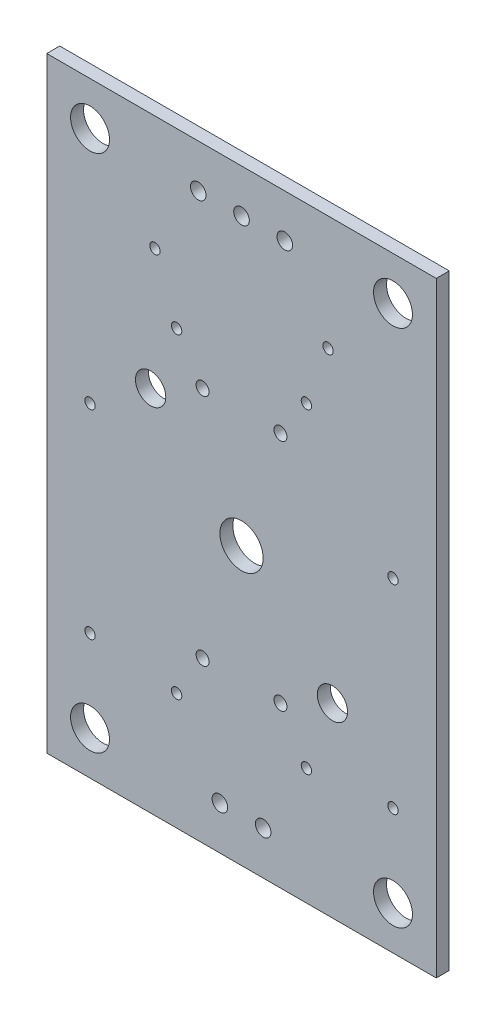
SolidWorks part; units mm, degrees
ref_plane "Спереди" through (0, 0, 0) normal (0, 0, 1) x (1, 0, 0)
ref_plane "Сверху" through (0, 0, 0) normal (0, 1, 0) x (1, 0, 0)
ref_plane "Справа" through (0, 0, 0) normal (1, 0, 0) x (0, 0, -1)
sketch "Эскиз1" plane through (0, 0, 0) normal (0, 0, 1) x (1, 0, 0)
  line L0 (0, 0) -> (72.8035, 0) construction
  line L1 (0, 0) -> (0, 51.7634) construction
  line L3 (-22.5, -35) -> (22.5, -35)
  line L4 (-22.5, -35) -> (-22.5, 35)
  line L5 (-22.5, 35) -> (22.5, 35)
  line L6 (22.5, -35) -> (22.5, 35)
  circle A0 centre (-17.5, 30) radius 2.25
  circle A1 centre (17.5, 30) radius 2.25
  circle A2 centre (17.5, -30) radius 2.25
  circle A3 centre (-17.5, -30) radius 2.25
  circle A4 centre (0, -3) radius 2.5
  circle A5 centre (-10.5, 7.5) radius 1.75
  circle A6 centre (10.5, -13.5) radius 1.75
  circle A7 centre (-5, 30) radius 0.9
  circle A8 centre (0, 30) radius 0.9
  circle A9 centre (5, 30) radius 0.9
  circle A10 centre (-2.5, -30) radius 0.9
  circle A11 centre (2.5, -30) radius 0.9
  circle A12 centre (-4.5, -16.5) radius 0.75
  circle A13 centre (-4.5, 10.5) radius 0.75
  circle A14 centre (4.5, -16.5) radius 0.75
  circle A15 centre (4.5, 10.5) radius 0.75
  dimension "D3" = 4.5
  dimension "D5" = 5
  dimension "D7" = 5
  dimension "D8" = 3.5
  dimension "D15" = 1.8
  dimension "D18" = 1.8
  dimension "D21" = 1.5
  dimension "D1" = 70
  dimension "D2" = 45
  dimension "D4" = 5
  dimension "D6" = 32
  dimension "D9" = 12
  dimension "D10" = 42.5
  dimension "D11" = 33
  dimension "D12" = 21.5
  dimension "D13" = 65
  dimension "D14" = 17.5
  dimension "D16" = 5
  dimension "D17" = 20
  dimension "D19" = 18
  dimension "D20" = 18.5
  dimension "D22" = 18
  dimension "D23" = 45.5
extrude "Вытянуть1" add sketch "Эскиз1" along normal blind 1.5
sketch "Эскиз2" plane through (0, 0, 1.5) normal (0, 0, 1) x (1, 0, 0)
  line L0 (0, 0) -> (0, 37.2524) construction
  line L1 (-22.5, 35) -> (-22.5, -35) construction
  line L2 (-22.5, -35) -> (22.5, -35) construction
  line L3 (-17.5, -20.5) -> (-17.5, -4.0913) construction
  circle A0 centre (-17.5, -20.5) radius 0.6
  circle A1 centre (-17.5, 2.5) radius 0.6
  circle A2 centre (17.5, 2.5) radius 0.6
  circle A3 centre (17.5, -20.5) radius 0.6
  circle A4 centre (-7.5, -21.5) radius 0.6
  circle A5 centre (7.5, -21.5) radius 0.6
  circle A6 centre (-7.5, 15) radius 0.6
  circle A7 centre (7.5, 15) radius 0.6
  circle A8 centre (-10, 21.75) radius 0.6
  circle A9 centre (10, 21.75) radius 0.6
  dimension "D1" = 1.2
  dimension "D4" = 37.5
  dimension "D7" = 12.5
  dimension "D8" = 1.2
  dimension "D9" = 50
  dimension "D10" = 15
  dimension "D11" = 1.2
  dimension "D2" = 5
  dimension "D3" = 14.5
  dimension "D5" = 13.5
  dimension "D6" = 15
  dimension "D12" = 56.75
extrude "Вырез-Вытянуть1" cut sketch "Эскиз2" against normal blind 1.5
